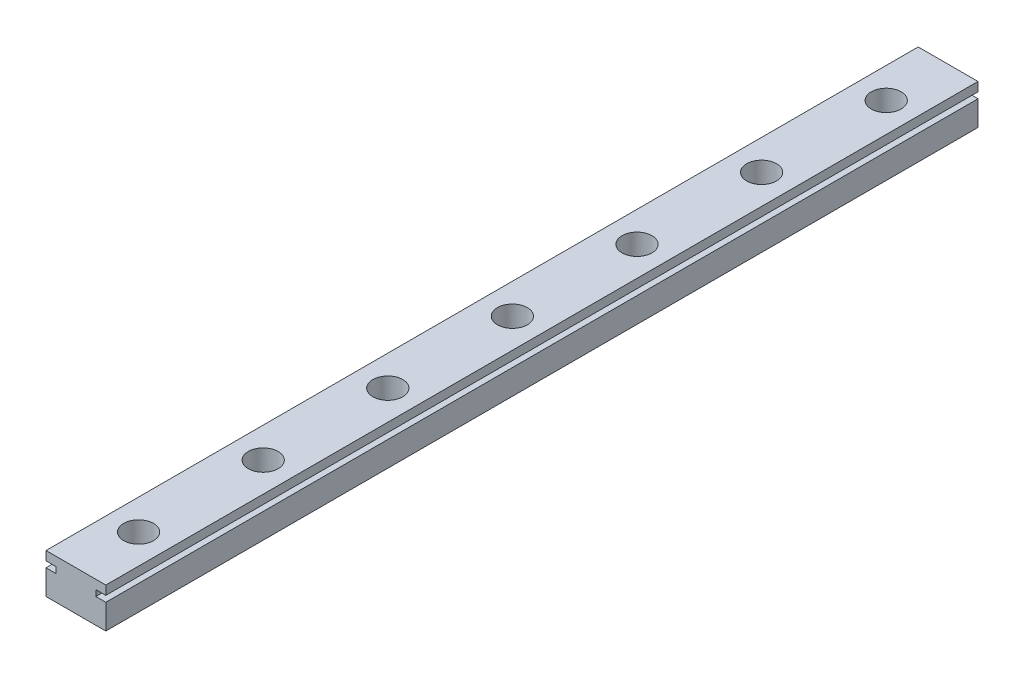
SolidWorks part; units mm, degrees
ref_plane "Plan de face" through (0, 0, 0) normal (0, 0, 1) x (1, 0, 0)
ref_plane "Plan de dessus" through (0, 0, 0) normal (0, 1, 0) x (1, 0, 0)
ref_plane "Plan de droite" through (0, 0, 0) normal (1, 0, 0) x (0, 0, -1)
sketch "Esquisse1" plane through (0, 0, 0) normal (0, 0, 1) x (1, 0, 0)
  line L0 (-2.288, -3.1489) -> (9.712, -3.1489)
  line L1 (9.712, -3.1489) -> (9.712, 1.8511)
  line L2 (9.712, 1.8511) -> (7.712, 1.8511)
  line L3 (7.712, 1.8511) -> (7.712, 3.0511)
  line L4 (7.712, 3.0511) -> (9.712, 3.0511)
  line L5 (9.712, 3.0511) -> (9.712, 4.8511)
  line L6 (9.712, 4.8511) -> (-2.288, 4.8511)
  line L7 (-2.288, 4.8511) -> (-2.288, 3.0511)
  line L8 (-2.288, 3.0511) -> (-0.288, 3.0511)
  line L9 (-0.288, 3.0511) -> (-0.288, 1.8511)
  line L10 (-0.288, 1.8511) -> (-2.288, 1.8511)
  line L11 (-2.288, 1.8511) -> (-2.288, -3.1489)
  dimension "D1" = 5
  dimension "D2" = 1.2
  dimension "D3" = 1.8
  dimension "D4" = 2
  dimension "D5" = 12
extrude "Boss.-Extru.1" add sketch "Esquisse1" along normal blind 175
sketch "Esquisse2" plane through (0, 4.8511, 0) normal (0, 1, 0) x (1, 0, 0)
  line L0 (9.712, -175) -> (-2.288, -175) construction
  circle A0 centre (3.7928, -162.5) radius 3
  circle A1 centre (3.7928, -137.5) radius 3
  circle A2 centre (3.7928, -112.5) radius 3
  circle A3 centre (3.7928, -87.5) radius 3
  circle A4 centre (3.7928, -62.5) radius 3
  circle A5 centre (3.7928, -37.5) radius 3
  circle A6 centre (3.7928, -12.5) radius 3
  circle A24 centre (3.7928, 412.5) radius 3 [skipped]
  circle A25 centre (3.7928, 387.5) radius 3 [skipped]
  circle A26 centre (3.7928, 362.5) radius 3 [skipped]
  circle A27 centre (3.7928, 12.5) radius 3 [skipped]
  circle A28 centre (3.7928, 37.5) radius 3 [skipped]
  circle A29 centre (3.7928, 62.5) radius 3 [skipped]
  circle A30 centre (3.7928, 87.5) radius 3 [skipped]
  circle A31 centre (3.7928, 112.5) radius 3 [skipped]
  circle A32 centre (3.7928, 137.5) radius 3 [skipped]
  circle A33 centre (3.7928, 162.5) radius 3 [skipped]
  circle A34 centre (3.7928, 187.5) radius 3 [skipped]
  circle A35 centre (3.7928, 212.5) radius 3 [skipped]
  circle A36 centre (3.7928, 237.5) radius 3 [skipped]
  circle A37 centre (3.7928, 262.5) radius 3 [skipped]
  circle A38 centre (3.7928, 287.5) radius 3 [skipped]
  circle A39 centre (3.7928, 312.5) radius 3 [skipped]
  circle A40 centre (3.7928, 337.5) radius 3 [skipped]
  dimension "D2" = 6
  dimension "D1" = 12.5
  dimension "D3" = 24
extrude "Enlèv. mat.-Extru.1" cut sketch "Esquisse2" against normal blind 4.5
sketch "Esquisse3" plane through (0, 0.3511, 0) normal (0, 1, 0) x (1, 0, 0)
  circle A0 centre (3.7928, -162.5) radius 1.75
  circle A1 centre (3.7928, -137.5) radius 1.75
  circle A2 centre (3.7928, -112.5) radius 1.75
  circle A3 centre (3.7928, -87.5) radius 1.75
  circle A4 centre (3.7928, -62.5) radius 1.75
  circle A5 centre (3.7928, -37.5) radius 1.75
  circle A6 centre (3.7928, -12.5) radius 1.75
  circle A24 centre (3.7928, 387.5) radius 1.75 [skipped]
  circle A25 centre (3.7928, 412.5) radius 1.75 [skipped]
  circle A26 centre (3.7928, 362.5) radius 1.75 [skipped]
  circle A27 centre (3.7928, 12.5) radius 1.75 [skipped]
  circle A28 centre (3.7928, 37.5) radius 1.75 [skipped]
  circle A29 centre (3.7928, 62.5) radius 1.75 [skipped]
  circle A30 centre (3.7928, 87.5) radius 1.75 [skipped]
  circle A31 centre (3.7928, 112.5) radius 1.75 [skipped]
  circle A32 centre (3.7928, 137.5) radius 1.75 [skipped]
  circle A33 centre (3.7928, 162.5) radius 1.75 [skipped]
  circle A34 centre (3.7928, 187.5) radius 1.75 [skipped]
  circle A35 centre (3.7928, 212.5) radius 1.75 [skipped]
  circle A36 centre (3.7928, 237.5) radius 1.75 [skipped]
  circle A37 centre (3.7928, 262.5) radius 1.75 [skipped]
  circle A38 centre (3.7928, 287.5) radius 1.75 [skipped]
  circle A39 centre (3.7928, 312.5) radius 1.75 [skipped]
  circle A40 centre (3.7928, 337.5) radius 1.75 [skipped]
  dimension "D1" = 3.5
  dimension "D2" = 24
extrude "Enlèv. mat.-Extru.2" cut sketch "Esquisse3" against normal up to next
sketch "Esquisse4" plane through (0, 0, 175) normal (0, 0, 1) x (1, 0, 0)
  line L0 (3.712, -3.1489) -> (3.712, 4.8511) construction
  line L1 (-2.288, -3.1489) -> (9.712, -3.1489) construction
  line L2 (9.712, 4.8511) -> (-2.288, 4.8511) construction
sketch "Esquisse5" plane through (0, 0, 0) normal (0, 0, -1) x (-1, 0, 0)
  line L0 (-3.712, 4.8511) -> (-3.712, -3.1489) construction
  line L1 (-9.712, 4.8511) -> (2.288, 4.8511) construction
  line L2 (2.288, -3.1489) -> (-9.712, -3.1489) construction
